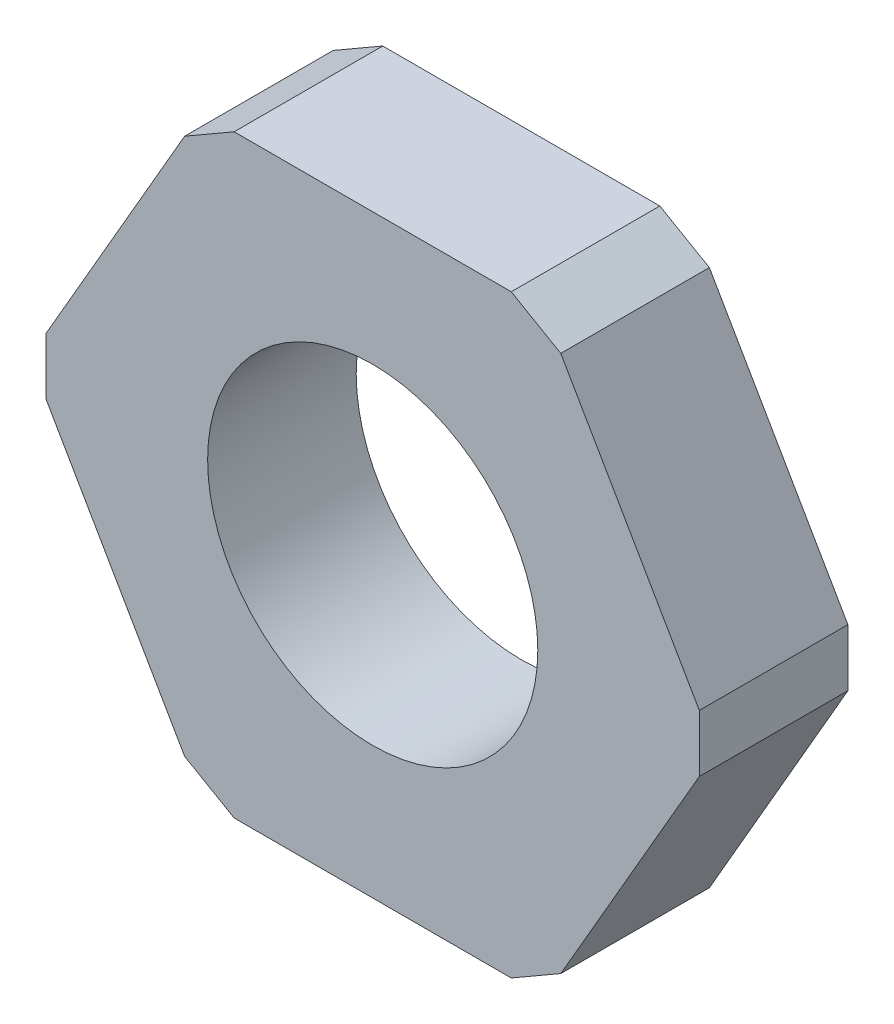
SolidWorks part; units mm, degrees
ref_plane "前基準面" through (0, 0, 0) normal (0, 0, 1) x (1, 0, 0)
ref_plane "上基準面" through (0, 0, 0) normal (0, 1, 0) x (1, 0, 0)
ref_plane "右基準面" through (0, 0, 0) normal (1, 0, 0) x (0, 0, -1)
sketch "草圖1" plane through (0, 0, 0) normal (0, 0, 1) x (1, 0, 0)
  line L0 (-99.8409, 2.85) -> (-99.8409, 31.5) construction
  line L1 (-77.9486, 21.066) -> (-82.1448, 28.334)
  line L2 (-83.6448, 29.2) -> (-92.0371, 29.2)
  line L3 (-93.5371, 28.334) -> (-97.7332, 21.066)
  line L4 (-97.7332, 19.334) -> (-93.5371, 12.066)
  line L5 (-92.0371, 11.2) -> (-83.6448, 11.2)
  line L6 (-82.1448, 12.066) -> (-77.9486, 19.334)
  line L7 (-20.403, 30.2) -> (-99.8409, 30.2) construction
  line L8 (-92.0371, 29.2) -> (-93.5371, 28.334)
  line L9 (-82.1448, 28.334) -> (-83.6448, 29.2)
  line L10 (-77.9486, 19.334) -> (-77.9486, 21.066)
  line L11 (-97.7332, 21.066) -> (-97.7332, 19.334)
  line L12 (-93.5371, 12.066) -> (-92.0371, 11.2)
  line L13 (-83.6448, 11.2) -> (-82.1448, 12.066)
  circle A0 centre (-87.8409, 20.2) radius 5
  circle A1 centre (-87.8409, 20.2) radius 9 construction
  point P3 (-77.4486, 20.2)
  point P4 (-82.6448, 29.2)
  point P5 (-93.0371, 29.2)
  point P6 (-98.2332, 20.2)
  point P7 (-93.0371, 11.2)
  point P8 (-82.6448, 11.2)
  dimension "D1" = 10
  dimension "D3" = 10
  dimension "D2" = 12
extrude "填料-伸長1" add sketch "草圖1" along normal blind 4.5
